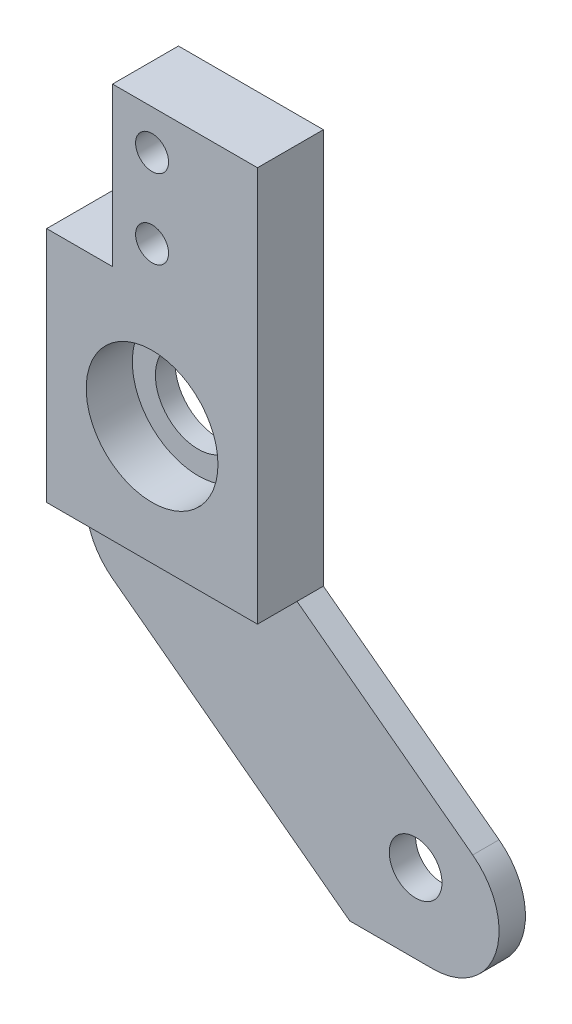
SolidWorks part; units mm, degrees
ref_plane "Front" through (0, 0, 0) normal (0, 0, 1) x (1, 0, 0)
ref_plane "Top" through (0, 0, 0) normal (0, 1, 0) x (1, 0, 0)
ref_plane "Right" through (0, 0, 0) normal (1, 0, 0) x (0, 0, -1)
sketch "Sketch1" plane through (0, 0, 0) normal (0, 0, 1) x (1, 0, 0)
  line L0 (-8, -13) -> (12, -28)
  line L2 (8, -9) -> (33.3333, -28)
  line L4 (-8, -13) -> (-8, 21)
  line L5 (-8, 21) -> (8, 21)
  line L6 (8, 21) -> (8, -9)
  line L8 (33.3333, -28) -> (12, -28)
  dimension "D1" = 34
  dimension "D2" = 15
  dimension "D3" = 20
  dimension "D5" = 8
  dimension "D7" = 21
  dimension "D4" = 16
  dimension "D6" = 30
extrude "Extrude1" add sketch "Sketch1" along normal blind 5
sketch "Sketch8" plane through (0, 0, 5) normal (0, 0, 1) x (1, 0, 0)
  circle A0 centre (0, 0) radius 5
  dimension "D1" = 10
extrude "Extrude6" cut sketch "Sketch8" against normal blind 3.5
sketch "Sketch9" plane through (0, 0, 1.5) normal (0, 0, 1) x (1, 0, 0)
  circle A0 centre (0, 0) radius 3.25
  dimension "D1" = 6.5
extrude "Extrude7" cut sketch "Sketch9" against normal up to surface (1.5 mm away) up to face at (7.5556, -6, 0)
sketch "Sketch11" plane through (0, 0, 0) normal (0, 0, -1) x (-1, 0, 0)
  line L0 (-8, 21) -> (-8, -9) construction
  line L1 (8, 21) -> (-8, 21) construction
  circle A0 centre (0, 18) radius 1.25
  circle A1 centre (0, 12) radius 1.25
  dimension "D1" = 8
  dimension "D2" = 2.5
  dimension "D3" = 2.5
  dimension "D4" = 8
  dimension "D5" = 3
  dimension "D6" = 6
sketch "Sketch14" plane through (0, 0, 5) normal (0, 0, 1) x (1, 0, 0)
  line L1 (-8, 21) -> (-3, 21)
  line L2 (-8, 21) -> (-8, 9)
  line L3 (-8, 9) -> (-3, 9)
  line L4 (-3, 21) -> (-3, 9)
  dimension "D1" = 5
  dimension "D2" = 12
extrude "Extrude12" cut sketch "Sketch14" against normal up to surface (5 mm away) up to face at (3.25, 0, 0)
extrude "Extrude9" cut sketch "Sketch11" against normal up to surface (5 mm away) up to face at (4.9167, -2.25, 5)
cosmetic thread "Hole Thread1" parameters "D1"=5, "D2"=3
cosmetic thread "Hole Thread2" parameters "D1"=5, "D2"=3
fillet "Fillet1" radius 5 2 edges at (33.3333, -28, 2.5) (-8, -13, 2.5)
sketch "Sketch12" plane through (0, 0, 5) normal (0, 0, 1) x (1, 0, 0)
  line L1 (18.3333, -28) -> (12, -28) construction
  line L5 (8, -9) -> (21.3333, -19) construction
  circle A0 centre (17, -22) radius 2
  dimension "D1" = 4
  dimension "D2" = 6
  dimension "D3" = 5
extrude "Extrude10" cut sketch "Sketch12" against normal up to surface (5 mm away) up to face at (-1.25, 12, 0)
sketch "Sketch13" plane through (0, 0, 5) normal (0, 0, 1) x (1, 0, 0)
  line L0 (12, -28) -> (18.3333, -28)
  line L1 (8, -9) -> (-8, -9)
  line L2 (21.3333, -19) -> (8, -9)
  line L3 (-8, -10.5) -> (-8, 9) construction
  line L4 (-8, -9) -> (-8, -10.5)
  line L5 (12, -28) -> (-6, -14.5)
  arc A0 (18.3333, -28) -> (21.3333, -19) centre (18.3333, -23) ccw
  arc A1 (-6, -14.5) -> (-8, -10.5) centre (-3, -10.5) cw
extrude "Extrude11" cut sketch "Sketch13" against normal blind 3
hole_wizard "M3 Tapped Hole1" positions "3DSketch1" profile "Sketch15" tap size "M3" standard "DIN"
sketch3d "3DSketch1"
  line L0 (0, 18, 5) -> (0, 18, 0) construction
  line L1 (0, 12, 5) -> (0, 12, 0) construction
  point P0 (0, 18, 5)
  point P4 (0, 12, 5)
sketch "Sketch15" plane through (0, 18, 5) normal (1, 0, 0) x (0, -1, 0)
  line L0 (0, 0) -> (0, 8.7511)
  line L1 (0, 8.7511) -> (1.25, 8)
  line L2 (1.25, 8) -> (1.25, 0)
  line L5 (1.25, 0) -> (0, 0)
  line L10 (0, 8.7511) -> (-1.25, 8) construction
  line L11 (0, -6.35) -> (0, 107.95) construction
  dimension "Tap Drill Dia." = 2.5
  dimension "Tap Drill Depth" = 8
  dimension "Drill Angle" = 118
